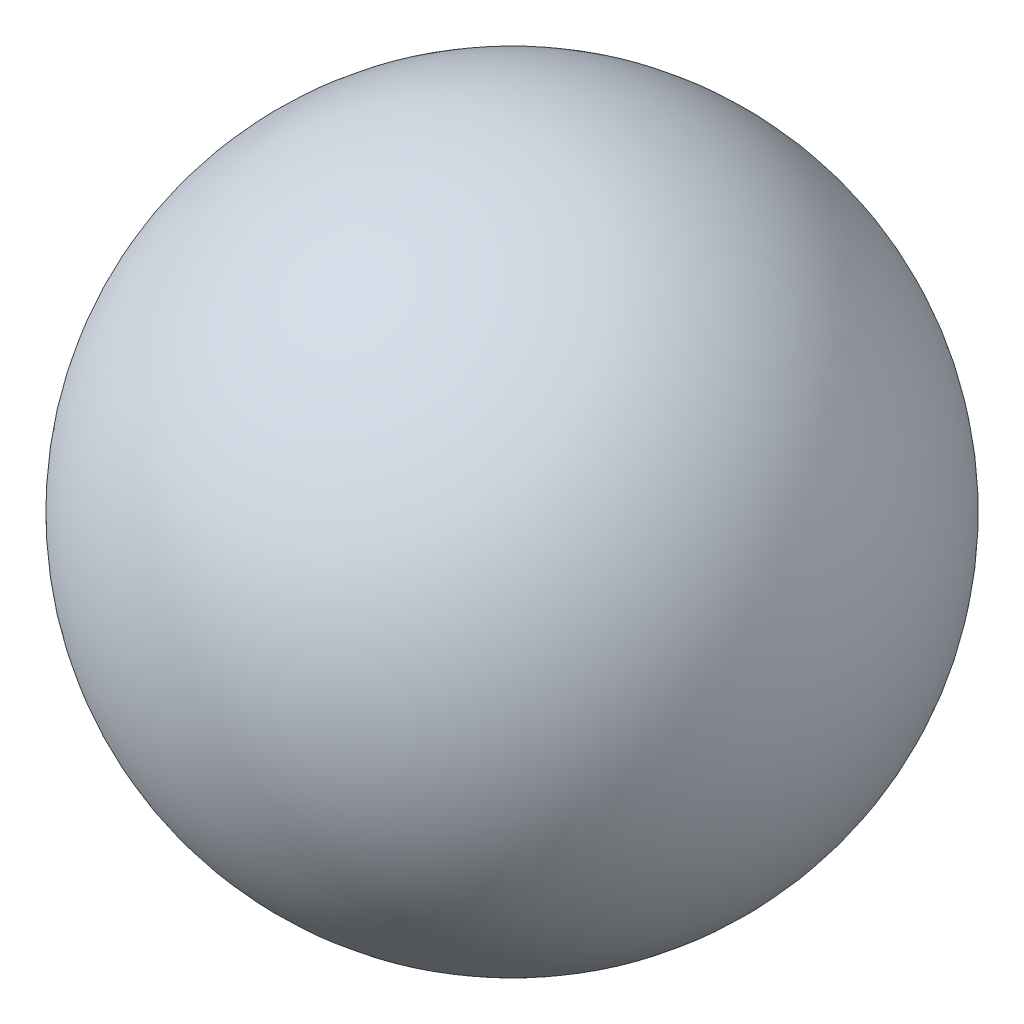
SolidWorks part; units mm, degrees
ref_plane "Front Plane" through (0, 0, 0) normal (0, 0, 1) x (1, 0, 0)
ref_plane "Top Plane" through (0, 0, 0) normal (0, 1, 0) x (1, 0, 0)
ref_plane "Right Plane" through (0, 0, 0) normal (1, 0, 0) x (0, 0, -1)
sketch "Sketch1" plane through (0, 0, 0) normal (0, 0, 1) x (1, 0, 0)
  line L0 (0, 4) -> (0, 0)
  line L1 (0, 0) -> (0, -4)
  arc A0 (0, 4) -> (0, -4) centre (0, 0) cw
  dimension "D1" = 4
revolve "Revolve1" add sketch "Sketch1" angle 360 about L1
sketch "Sketch4" plane through (0, 0, 0) normal (0, 0, 1) x (1, 0, 0)
  circle A0 centre (0, 0) radius 4 construction
  point P0 (0, 4)
  point P1 (0, -4)
